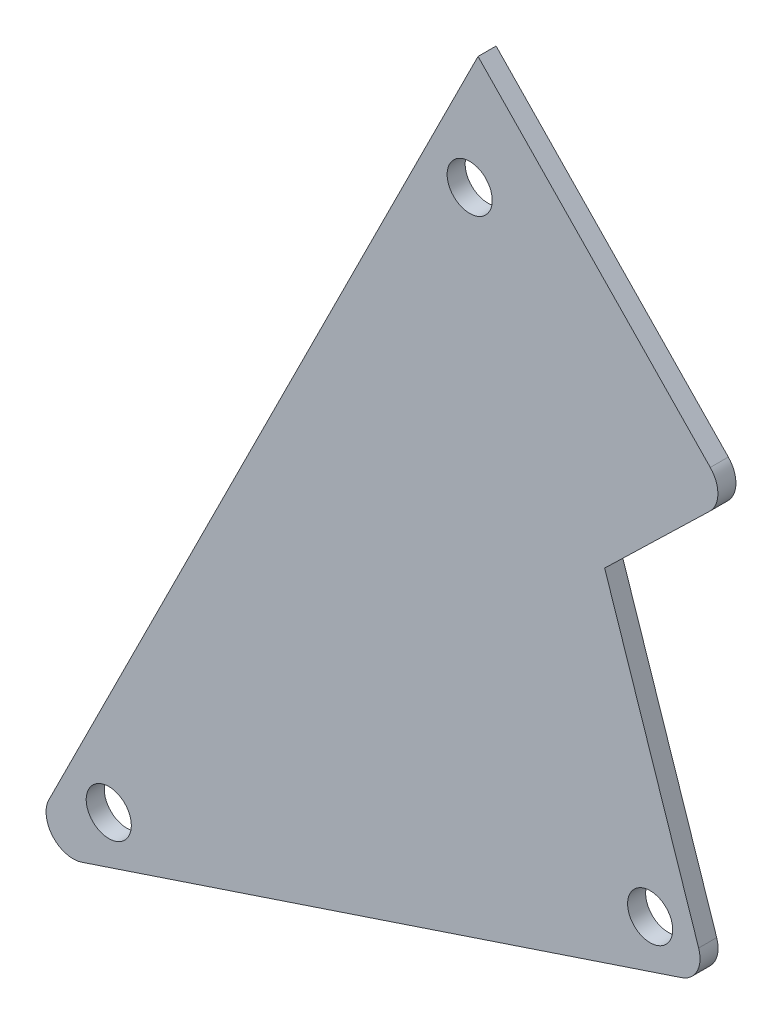
SolidWorks part; units mm, degrees
ref_plane "Front Plane" through (0, 0, 0) normal (0, 0, 1) x (1, 0, 0)
ref_plane "Top Plane" through (0, 0, 0) normal (0, 1, 0) x (1, 0, 0)
ref_plane "Right Plane" through (0, 0, 0) normal (1, 0, 0) x (0, 0, -1)
sketch "Sketch1" plane through (0, 0, 0) normal (0, 0, 1) x (1, 0, 0)
  line L0 (-76.2, 0) -> (0, 0) construction
  line L1 (0, 0) -> (0, 25.4) construction
  line L2 (0, 25.4) -> (0, 101.6) construction
  line L3 (0, 101.6) -> (-25.4, 101.6) construction
  line L4 (-24.2237, 118.1516) -> (-88.7355, -10.872)
  line L5 (-76.2, 0) -> (-25.4, 101.6) construction
  line L6 (-25.4, 101.6) -> (0, 25.4) construction
  line L7 (0, 25.4) -> (-76.2, 0) construction
  line L8 (-88.7355, -10.872) -> (8.0322, 21.3839)
  line L9 (8.0322, 21.3839) -> (-24.2237, 118.1516) construction
  line L10 (-24.2237, 118.1516) -> (11.1136, 81.6562)
  line L12 (11.1136, 81.6562) -> (-6.4045, 64.694)
  line L13 (-6.4045, 64.694) -> (8.0322, 21.3839)
  circle A0 centre (-76.2, 0) radius 3.175
  circle A1 centre (0, 25.4) radius 3.175
  circle A2 centre (-25.4, 101.6) radius 3.175
  dimension "D5" = 6.35
  dimension "D6" = 6.35
  dimension "D7" = 6.35
  dimension "D1" = 76.2
  dimension "D2" = 25.4
  dimension "D3" = 76.2
  dimension "D4" = 25.4
  dimension "D8" = 6.35
  dimension "D9" = 6.35
  dimension "D10" = 6.35
  dimension "D11" = 25.641
  dimension "D12" = 50.8
extrude "Boss-Extrude1" add sketch "Sketch1" along normal blind 2.54
fillet "Fillet1" radius 3.81 3 edges at (-88.7355, -10.872, 1.27) (8.0322, 21.3839, 1.27) (11.1136, 81.6562, 1.27)
